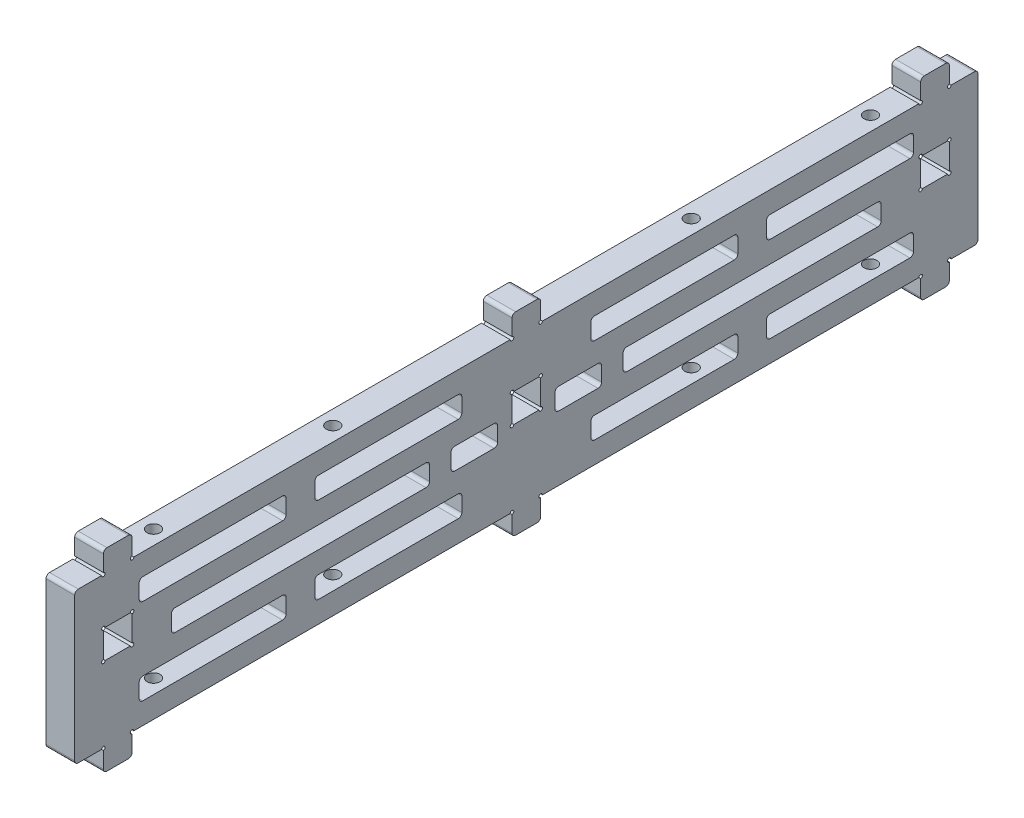
SolidWorks part; units mm, degrees
ref_plane "前视基准面" through (0, 0, 0) normal (0, 0, 1) x (1, 0, 0)
ref_plane "上视基准面" through (0, 0, 0) normal (0, 1, 0) x (1, 0, 0)
ref_plane "右视基准面" through (0, 0, 0) normal (1, 0, 0) x (0, 0, -1)
sketch "草图1" plane through (0, 0, 0) normal (1, 0, 0) x (0, 0, -1)
  line L0 (0, 2) -> (0, 0) construction
  line L1 (-63, 10.5) -> (63, 10.5)
  line L2 (-63, 10.5) -> (-63, -10.5)
  line L3 (-63, -10.5) -> (63, -10.5)
  line L4 (63, 10.5) -> (63, -10.5)
  line L5 (-63, 10.5) -> (63, -10.5) construction
  line L6 (-63, -10.5) -> (63, 10.5) construction
  line L7 (-2, 4) -> (2, 4)
  line L8 (-2, 4) -> (-2, 0)
  line L9 (-2, 0) -> (2, 0)
  line L10 (2, 4) -> (2, 0)
  line L11 (-2, 4) -> (2, 0) construction
  line L12 (-2, 0) -> (2, 4) construction
  line L13 (0, 2) -> (57, 2) construction
  line L14 (55, 4) -> (59, 4)
  line L15 (55, 4) -> (55, 0)
  line L16 (55, 0) -> (59, 0)
  line L17 (59, 4) -> (59, 0)
  line L18 (55, 4) -> (59, 0) construction
  line L19 (55, 0) -> (59, 4) construction
  line L20 (-55, 0) -> (-59, 0)
  line L21 (-59, 4) -> (-59, 0)
  line L22 (-55, 4) -> (-59, 4)
  line L23 (-55, 4) -> (-55, 0)
  point P1 (0, 0)
  point P6 (0, 2)
  point P11 (57, 2)
  dimension "D1" = 126
  dimension "D2" = 21
  dimension "D3" = 4
  dimension "D4" = 4
  dimension "D5" = 2
  dimension "D6" = 4
  dimension "D7" = 4
  dimension "D8" = 57
extrude "凸台-拉伸1" add sketch "草图1" along normal blind 4
sketch "草图2" plane through (4, 0, 0) normal (1, 0, 0) x (0, 0, -1)
  line L0 (0, 0) -> (0, 12) construction
  line L1 (-1.5, 13.5) -> (1.5, 13.5)
  line L2 (-2, 13) -> (-2, 10.5)
  line L3 (-2, 10.5) -> (2, 10.5)
  line L4 (2, 13) -> (2, 10.5)
  line L5 (-2, 13.5) -> (2, 10.5) construction
  line L6 (-2, 10.5) -> (2, 13.5) construction
  line L7 (63, 10.5) -> (-63, 10.5) construction
  line L8 (57, 12) -> (57, 4) construction
  line L9 (55.5, 13.5) -> (58.5, 13.5)
  line L10 (55, 13) -> (55, 10.5)
  line L11 (55, 10.5) -> (59, 10.5)
  line L12 (59, 13) -> (59, 10.5)
  line L13 (55, 13.5) -> (59, 10.5) construction
  line L14 (55, 10.5) -> (59, 13.5) construction
  line L15 (59, 4) -> (55, 4) construction
  line L16 (-55, 10.5) -> (-59, 10.5)
  line L17 (-59, 13) -> (-59, 10.5)
  line L18 (-55.5, 13.5) -> (-58.5, 13.5)
  line L19 (-55, 13) -> (-55, 10.5)
  line L20 (0, 0) -> (17.3325, 0) construction
  line L21 (-55.5, -13.5) -> (-58.5, -13.5)
  line L22 (-55, -13) -> (-55, -10.5)
  line L23 (-55, -10.5) -> (-59, -10.5)
  line L24 (-59, -13) -> (-59, -10.5)
  line L25 (-2, -10.5) -> (2, -10.5)
  line L26 (2, -13) -> (2, -10.5)
  line L27 (-1.5, -13.5) -> (1.5, -13.5)
  line L28 (-2, -13) -> (-2, -10.5)
  line L29 (55, -10.5) -> (59, -10.5)
  line L30 (59, -13) -> (59, -10.5)
  line L31 (55.5, -13.5) -> (58.5, -13.5)
  line L32 (55, -13) -> (55, -10.5)
  arc A0 (-1.5, 13.5) -> (-2, 13) centre (-1.5, 13) ccw
  arc A1 (1.5, 13.5) -> (2, 13) centre (1.5, 13) cw
  arc A2 (55.5, 13.5) -> (55, 13) centre (55.5, 13) ccw
  arc A3 (58.5, 13.5) -> (59, 13) centre (58.5, 13) cw
  arc A4 (-58.5, 13.5) -> (-59, 13) centre (-58.5, 13) ccw
  arc A5 (-55.5, 13.5) -> (-55, 13) centre (-55.5, 13) cw
  arc A6 (-55.5, -13.5) -> (-55, -13) centre (-55.5, -13) ccw
  arc A7 (-58.5, -13.5) -> (-59, -13) centre (-58.5, -13) cw
  arc A8 (1.5, -13.5) -> (2, -13) centre (1.5, -13) ccw
  arc A9 (-1.5, -13.5) -> (-2, -13) centre (-1.5, -13) cw
  arc A10 (58.5, -13.5) -> (59, -13) centre (58.5, -13) ccw
  arc A11 (55.5, -13.5) -> (55, -13) centre (55.5, -13) cw
  point P0 (0, 12)
  point P16 (57, 12)
  dimension "D3" = 0.5
  dimension "D6" = 0.5
  dimension "D1" = 4
  dimension "D2" = 3
  dimension "D4" = 3
  dimension "D5" = 4
extrude "凸台-拉伸2" add sketch "草图2" against normal blind 4
sketch "草图3" plane through (4, 0, 0) normal (1, 0, 0) x (0, 0, -1)
  line L0 (0, 0) -> (0, 7.3296) construction
  line L1 (0, 0) -> (10.3553, 0) construction
  circle A0 centre (59, 10.5) radius 0.25
  circle A1 centre (55, 10.5) radius 0.25
  circle A2 centre (2, 10.5) radius 0.25
  circle A3 centre (-2, 10.5) radius 0.25
  circle A4 centre (-55, 10.5) radius 0.25
  circle A5 centre (-59, 10.5) radius 0.25
  circle A6 centre (-59, -10.5) radius 0.25
  circle A7 centre (-55, -10.5) radius 0.25
  circle A8 centre (-2, -10.5) radius 0.25
  circle A9 centre (2, -10.5) radius 0.25
  circle A10 centre (55, -10.5) radius 0.25
  circle A11 centre (59, -10.5) radius 0.25
  circle A12 centre (-55, 0) radius 0.25
  circle A13 centre (-55, 4) radius 0.25
  circle A14 centre (-59, 4) radius 0.25
  circle A15 centre (-59, 0) radius 0.25
  circle A16 centre (-2, 0) radius 0.25
  circle A17 centre (-2, 4) radius 0.25
  circle A18 centre (59, 4) radius 0.25
  circle A19 centre (59, 0) radius 0.25
  circle A20 centre (55, 0) radius 0.25
  circle A21 centre (55, 4) radius 0.25
  circle A22 centre (2, 4) radius 0.25
  circle A23 centre (2, 0) radius 0.25
  dimension "D1" = 0.5
  dimension "D2" = 0.5
  dimension "D3" = 0.5
  dimension "D4" = 0.5
  dimension "D5" = 0.5
  dimension "D6" = 0.5
  dimension "D7" = 0.5
  dimension "D8" = 0.5
  dimension "D9" = 0.5
extrude "切除-拉伸1" cut sketch "草图3" against normal blind 4
sketch "草图4" plane through (4, 0, 0) normal (1, 0, 0) x (0, 0, -1)
  line L0 (0, 0) -> (-63, 0) construction
  line L1 (-53.5, 7.5) -> (-34, 7.5)
  line L2 (-54, 7) -> (-54, 5)
  line L3 (-53.5, 4.5) -> (-34, 4.5)
  line L4 (-33.5, 7) -> (-33.5, 5)
  line L5 (-54, 7.5) -> (-33.5, 4.5) construction
  line L6 (-54, 4.5) -> (-33.5, 7.5) construction
  line L7 (-63, 10.5) -> (-63, -10.5) construction
  line L8 (-31.5, 0) -> (-31.5, 8.4299) construction
  line L9 (-9.5, 4.5) -> (-29, 4.5)
  line L10 (-29.5, 7) -> (-29.5, 5)
  line L11 (-9.5, 7.5) -> (-29, 7.5)
  line L12 (-9, 7) -> (-9, 5)
  line L13 (-53.5, -4.5) -> (-34, -4.5)
  line L14 (-33.5, -7) -> (-33.5, -5)
  line L15 (-53.5, -7.5) -> (-34, -7.5)
  line L16 (-54, -7) -> (-54, -5)
  line L17 (-9.5, -4.5) -> (-29, -4.5)
  line L18 (-9, -7) -> (-9, -5)
  line L19 (-9.5, -7.5) -> (-29, -7.5)
  line L20 (-29.5, -7) -> (-29.5, -5)
  line L21 (-2, 3.75) -> (-2, 0.25) construction
  line L22 (-2.25, 10.5) -> (-54.75, 10.5) construction
  line L24 (-49, 1.5) -> (-14, 1.5)
  line L25 (-49.5, 1) -> (-49.5, -1)
  line L26 (-49, -1.5) -> (-14, -1.5)
  line L27 (-13.5, 1) -> (-13.5, -1)
  line L28 (-49.5, 1.5) -> (-13.5, -1.5) construction
  line L29 (-49.5, -1.5) -> (-13.5, 1.5) construction
  line L30 (-10, 1.5) -> (-4.5, 1.5)
  line L31 (-10.5, 1) -> (-10.5, -1)
  line L32 (-10, -1.5) -> (-4.5, -1.5)
  line L33 (-4, 1) -> (-4, -1)
  line L34 (-10.5, 1.5) -> (-4, -1.5) construction
  line L35 (-10.5, -1.5) -> (-4, 1.5) construction
  line L39 (0, 0) -> (0, 6.5084) construction
  line L40 (49, -1.5) -> (14, -1.5)
  line L41 (13.5, 1) -> (13.5, -1)
  line L42 (49, 1.5) -> (14, 1.5)
  line L43 (49.5, 1) -> (49.5, -1)
  line L44 (10, -1.5) -> (4.5, -1.5)
  line L45 (4, 1) -> (4, -1)
  line L46 (10, 1.5) -> (4.5, 1.5)
  line L47 (10.5, 1) -> (10.5, -1)
  line L48 (9, -7) -> (9, -5)
  line L49 (9.5, -7.5) -> (29, -7.5)
  line L50 (29.5, -7) -> (29.5, -5)
  line L51 (9.5, -4.5) -> (29, -4.5)
  line L52 (53.5, -4.5) -> (34, -4.5)
  line L53 (54, -7) -> (54, -5)
  line L54 (53.5, -7.5) -> (34, -7.5)
  line L55 (33.5, -7) -> (33.5, -5)
  line L56 (53.5, 4.5) -> (34, 4.5)
  line L57 (33.5, 7) -> (33.5, 5)
  line L58 (53.5, 7.5) -> (34, 7.5)
  line L59 (54, 7) -> (54, 5)
  line L60 (9.5, 4.5) -> (29, 4.5)
  line L61 (9, 7) -> (9, 5)
  line L62 (9.5, 7.5) -> (29, 7.5)
  line L63 (29.5, 7) -> (29.5, 5)
  arc A0 (-53.5, 7.5) -> (-54, 7) centre (-53.5, 7) ccw
  arc A1 (-54, 5) -> (-53.5, 4.5) centre (-53.5, 5) ccw
  arc A2 (-34, 4.5) -> (-33.5, 5) centre (-34, 5) ccw
  arc A3 (-34, 7.5) -> (-33.5, 7) centre (-34, 7) cw
  arc A4 (-29, 4.5) -> (-29.5, 5) centre (-29, 5) cw
  arc A5 (-29, 7.5) -> (-29.5, 7) centre (-29, 7) ccw
  arc A6 (-9.5, 7.5) -> (-9, 7) centre (-9.5, 7) cw
  arc A7 (-9, 5) -> (-9.5, 4.5) centre (-9.5, 5) cw
  arc A8 (-34, -4.5) -> (-33.5, -5) centre (-34, -5) cw
  arc A9 (-34, -7.5) -> (-33.5, -7) centre (-34, -7) ccw
  arc A10 (-53.5, -7.5) -> (-54, -7) centre (-53.5, -7) cw
  arc A11 (-54, -5) -> (-53.5, -4.5) centre (-53.5, -5) cw
  arc A12 (-9, -5) -> (-9.5, -4.5) centre (-9.5, -5) ccw
  arc A13 (-9.5, -7.5) -> (-9, -7) centre (-9.5, -7) ccw
  arc A14 (-29, -7.5) -> (-29.5, -7) centre (-29, -7) cw
  arc A15 (-29, -4.5) -> (-29.5, -5) centre (-29, -5) ccw
  arc A16 (-10, 1.5) -> (-10.5, 1) centre (-10, 1) ccw
  arc A17 (-10.5, -1) -> (-10, -1.5) centre (-10, -1) ccw
  arc A18 (-4.5, -1.5) -> (-4, -1) centre (-4.5, -1) ccw
  arc A19 (-4.5, 1.5) -> (-4, 1) centre (-4.5, 1) cw
  arc A24 (-49, 1.5) -> (-49.5, 1) centre (-49, 1) ccw
  arc A25 (-49.5, -1) -> (-49, -1.5) centre (-49, -1) ccw
  arc A26 (-14, -1.5) -> (-13.5, -1) centre (-14, -1) ccw
  arc A27 (-14, 1.5) -> (-13.5, 1) centre (-14, 1) cw
  arc A28 (14, -1.5) -> (13.5, -1) centre (14, -1) cw
  arc A29 (14, 1.5) -> (13.5, 1) centre (14, 1) ccw
  arc A30 (49, 1.5) -> (49.5, 1) centre (49, 1) cw
  arc A31 (49.5, -1) -> (49, -1.5) centre (49, -1) cw
  arc A32 (4.5, -1.5) -> (4, -1) centre (4.5, -1) cw
  arc A33 (4.5, 1.5) -> (4, 1) centre (4.5, 1) ccw
  arc A34 (10, 1.5) -> (10.5, 1) centre (10, 1) cw
  arc A35 (10.5, -1) -> (10, -1.5) centre (10, -1) cw
  arc A36 (9.5, -7.5) -> (9, -7) centre (9.5, -7) cw
  arc A37 (29, -7.5) -> (29.5, -7) centre (29, -7) ccw
  arc A38 (29, -4.5) -> (29.5, -5) centre (29, -5) cw
  arc A39 (9, -5) -> (9.5, -4.5) centre (9.5, -5) cw
  arc A40 (54, -5) -> (53.5, -4.5) centre (53.5, -5) ccw
  arc A41 (53.5, -7.5) -> (54, -7) centre (53.5, -7) ccw
  arc A42 (34, -7.5) -> (33.5, -7) centre (34, -7) cw
  arc A43 (34, -4.5) -> (33.5, -5) centre (34, -5) ccw
  arc A44 (34, 4.5) -> (33.5, 5) centre (34, 5) cw
  arc A45 (34, 7.5) -> (33.5, 7) centre (34, 7) ccw
  arc A46 (53.5, 7.5) -> (54, 7) centre (53.5, 7) cw
  arc A47 (54, 5) -> (53.5, 4.5) centre (53.5, 5) cw
  arc A48 (9, 5) -> (9.5, 4.5) centre (9.5, 5) ccw
  arc A49 (9.5, 7.5) -> (9, 7) centre (9.5, 7) ccw
  arc A50 (29, 7.5) -> (29.5, 7) centre (29, 7) cw
  arc A51 (29, 4.5) -> (29.5, 5) centre (29, 5) ccw
  point P0 (-43.75, 6)
  point P68 (-7.25, 0)
  point P73 (-2, 2)
  dimension "D1" = 0.5
  dimension "D7" = 0.5
  dimension "D12" = 0.5
  dimension "D2" = 7
  dimension "D3" = 4
  dimension "D4" = 3
  dimension "D5" = 3
  dimension "D6" = 2
  dimension "D8" = 3
  dimension "D9" = 3
  dimension "D10" = 3
  dimension "D11" = 36
extrude "切除-拉伸2" cut sketch "草图4" against normal blind 4
fillet "圆角1" radius 0.5 4 edges at (2, -10.5, -63) (2, 10.5, -63) (2, -10.5, 63) (2, 10.5, 63)
sketch "草图5" plane through (0, 10.5, 0) normal (0, 1, 0) x (1, 0, 0)
  line L0 (2, 2.25) -> (2, 25) construction
  line L1 (0, 2.25) -> (4, 2.25) construction
  line L2 (2, 25) -> (2, 50) construction
  line L3 (0, 0) -> (7.2822, 0) construction
  circle A0 centre (2, 25) radius 0.9
  circle A1 centre (2, 50) radius 0.9
  circle A2 centre (2, -50) radius 0.9
  circle A3 centre (2, -25) radius 0.9
  dimension "D1" = 1.8
  dimension "D3" = 1.8
  dimension "D2" = 25
  dimension "D4" = 25
extrude "切除-拉伸3" cut sketch "草图5" against normal up to next
mirror "镜向1" about plane through (0, 0, 0) normal (0, 1, 0) of "切除-拉伸3"
